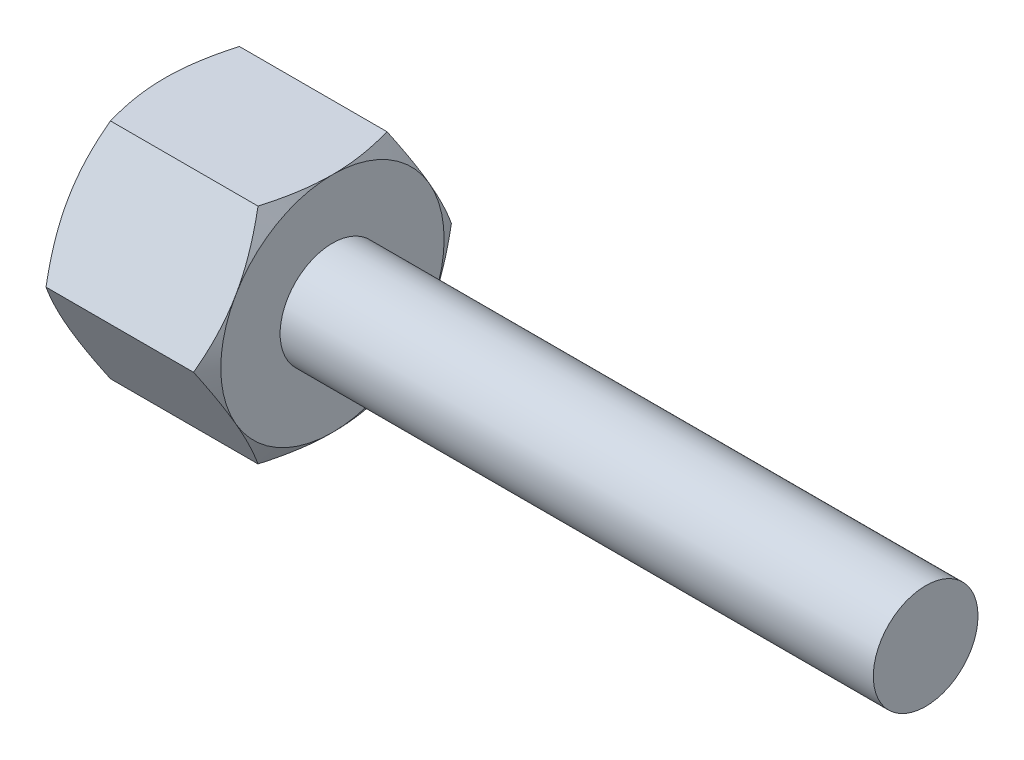
SolidWorks part; units mm, degrees
ref_plane "Ön Düzlem" through (0, 0, 0) normal (0, 0, 1) x (1, 0, 0)
ref_plane "Üst Düzlem" through (0, 0, 0) normal (0, 1, 0) x (1, 0, 0)
ref_plane "Sağ Düzlem" through (0, 0, 0) normal (1, 0, 0) x (0, 0, -1)
sketch "Çizim1" plane through (0, 0, 0) normal (1, 0, 0) x (0, 0, -1)
  line L1 (4.6188, 0) -> (2.3094, 4)
  line L2 (2.3094, 4) -> (-2.3094, 4)
  line L3 (-2.3094, 4) -> (-4.6188, 0)
  line L4 (-4.6188, 0) -> (-2.3094, -4)
  line L5 (-2.3094, -4) -> (2.3094, -4)
  line L6 (2.3094, -4) -> (4.6188, 0)
  circle A0 centre (0, 0) radius 4 construction
  dimension "D1" = 8
extrude "Yükseklik-Ekstrüzyon1" add sketch "Çizim1" along normal blind 6
sketch "Çizim2" plane through (6, 0, 0) normal (1, 0, 0) x (0, 0, -1)
  circle A0 centre (0, 0) radius 1.875
  dimension "D1" = 3.75
extrude "Yükseklik-Ekstrüzyon2" add sketch "Çizim2" along normal blind 21.25
sketch "Çizim3" plane through (6, 0, 0) normal (1, 0, 0) x (0, 0, -1)
  circle A0 centre (0, 0) radius 4
extrude "Kes-Ekstrüzyon1" cut sketch "Çizim3" against normal blind 10 draft 60 flip side to cut
sketch "Çizim4" plane through (0, 0, 0) normal (-1, 0, 0) x (0, 0, 1)
  circle A0 centre (0, 0) radius 4
extrude "Kes-Ekstrüzyon2" cut sketch "Çizim4" against normal blind 10 draft 60 flip side to cut
